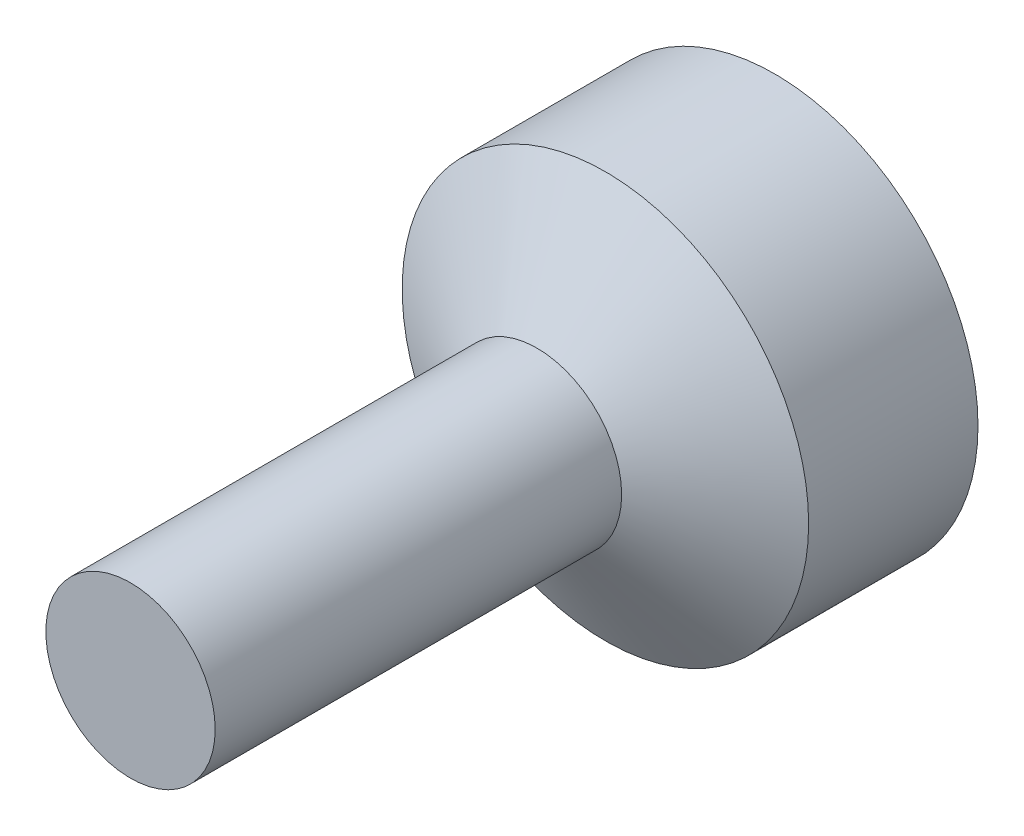
SolidWorks part; units mm, degrees
ref_plane "Front Plane" through (0, 0, 0) normal (0, 0, 1) x (1, 0, 0)
ref_plane "Top Plane" through (0, 0, 0) normal (0, 1, 0) x (1, 0, 0)
ref_plane "Right Plane" through (0, 0, 0) normal (1, 0, 0) x (0, 0, -1)
sketch "Sketch1" plane through (0, 0, 0) normal (0, 1, 0) x (1, 0, 0)
  line L0 (0, 0) -> (3.048, 0)
  line L1 (3.048, 0) -> (3.048, -2.54)
  line L2 (3.048, -2.54) -> (1.27, -3.5665)
  line L3 (1.27, -3.5665) -> (1.27, -9.6625)
  line L4 (1.27, -9.6625) -> (0, -9.6625)
  line L5 (0, -9.6625) -> (0, 0)
  point P3 (4.5721, -2.54)
  point P8 (0, 0)
  dimension "D1" = 6.096
  dimension "D2" = 2.54
  dimension "D3" = 3.048
  dimension "D4" = 1.27
  dimension "D5" = 120
revolve "Revolve1" add sketch "Sketch1" angle 360 about L5
